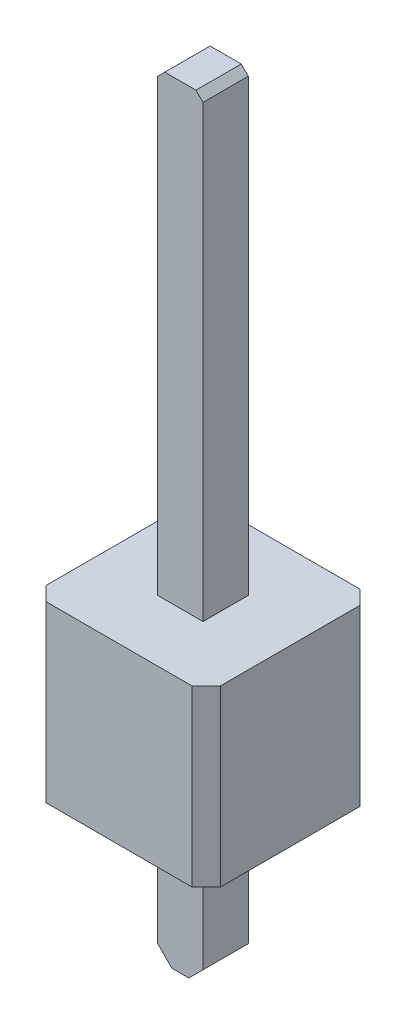
SolidWorks part; units mm, degrees
ref_plane "Alzado" through (0, 0, 0) normal (0, 0, 1) x (1, 0, 0)
ref_plane "Planta" through (0, 0, 0) normal (0, 1, 0) x (1, 0, 0)
ref_plane "Vista lateral" through (0, 0, 0) normal (1, 0, 0) x (0, 0, -1)
sketch "Croquis1" plane through (0, 0, 0) normal (0, 0, 1) x (1, 0, 0)
  line L1 (-34.7731, -32.8044) -> (-37.2331, -32.8044)
  line L2 (-34.7731, -32.8044) -> (-34.7731, -30.3444)
  line L3 (-34.7731, -30.3444) -> (-37.2331, -30.3444)
  line L4 (-37.2331, -32.8044) -> (-37.2331, -30.3444)
  point P0 (0, 0)
extrude "Saliente-Extruir1" add sketch "Croquis1" along normal blind 2.37
sketch "Croquis2" plane through (0, -30.3444, 0) normal (0, 1, 0) x (1, 0, 0)
  line L4 (-35.6831, -1.505) -> (-36.3231, -1.505)
  line L5 (-35.6831, -1.505) -> (-35.6831, -0.865)
  line L6 (-35.6831, -0.865) -> (-36.3231, -0.865)
  line L7 (-36.3231, -1.505) -> (-36.3231, -0.865)
extrude "Saliente-Extruir2" add sketch "Croquis2" along normal blind 6.45
sketch "Croquis3" plane through (0, -32.8044, 0) normal (0, -1, 0) x (1, 0, 0)
  line L4 (-35.6831, 1.505) -> (-36.3231, 1.505)
  line L5 (-35.6831, 1.505) -> (-35.6831, 0.865)
  line L6 (-35.6831, 0.865) -> (-36.3231, 0.865)
  line L7 (-36.3231, 1.505) -> (-36.3231, 0.865)
extrude "Saliente-Extruir3" add sketch "Croquis3" along normal blind 2
chamfer "Chaflán1" distance 0.2 angle 45 1 edges at (-37.2331, -31.5744, 2.37)
chamfer "Chaflán2" distance 0.2 angle 45 1 edges at (-34.7731, -31.5744, 2.37)
chamfer "Chaflán3" distance 0.2 angle 45 1 edges at (-34.7731, -31.5744, 0)
chamfer "Chaflán4" distance 0.2 angle 45 1 edges at (-37.2331, -31.5744, 0)
chamfer "Chaflán5" distance 0.1 angle 45 1 edges at (-35.6831, -23.8944, 1.185)
chamfer "Chaflán6" distance 0.1 angle 45 1 edges at (-36.3231, -23.8944, 1.185)
chamfer "Chaflán7" distance 0.2 angle 45 1 edges at (-35.6831, -34.8044, 1.185)
chamfer "Chaflán8" distance 0.2 angle 45 1 edges at (-36.3231, -34.8044, 1.185)
